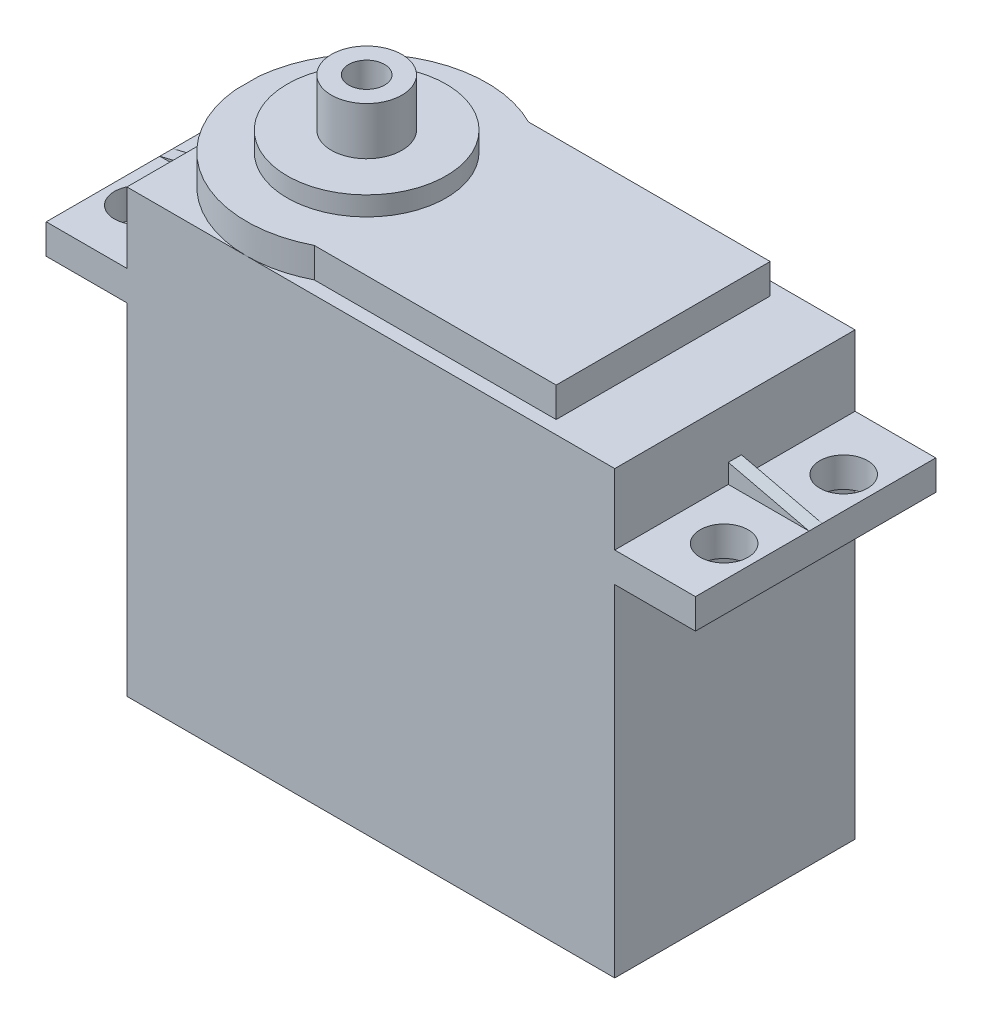
SolidWorks part; units mm, degrees
ref_plane "Plan de face" through (0, 0, 0) normal (0, 0, 1) x (1, 0, 0)
ref_plane "Plan de dessus" through (0, 0, 0) normal (0, 1, 0) x (1, 0, 0)
ref_plane "Plan de droite" through (0, 0, 0) normal (1, 0, 0) x (0, 0, -1)
sketch "Esquisse1" plane through (0, 0, 0) normal (0, 0, 1) x (1, 0, 0)
  line L0 (0, 0) -> (0, 3.4659) construction
  line L1 (-20.4, 10.9) -> (20.4, 10.9)
  line L2 (-20.4, 10.9) -> (-20.4, -28.5)
  line L3 (-20.4, -28.5) -> (20.4, -28.5)
  line L4 (20.4, 10.9) -> (20.4, -28.5)
  line L5 (-20.4, 2.5) -> (-27.15, 2.5)
  line L6 (-20.4, 2.5) -> (-20.4, 0)
  line L7 (-20.4, 0) -> (-27.15, 0)
  line L8 (-27.15, 2.5) -> (-27.15, 0)
  line L9 (20.4, 0) -> (27.15, 0)
  line L10 (27.15, 2.5) -> (27.15, 0)
  line L11 (20.4, 2.5) -> (27.15, 2.5)
  line L12 (20.4, 2.5) -> (20.4, 0)
  point P4 (0, 10.9)
  dimension "D1" = 2.5
  dimension "D2" = 54.3
  dimension "D3" = 40.8
  dimension "D4" = 28.5
  dimension "D5" = 39.4
extrude "Boss.-Extru.1" add sketch "Esquisse1" along normal mid plane 20.1
hole_wizard "Diamètre du perçage Ø4.0 (4)1" positions "Esquisse2" profile "Esquisse3" hole size "Ø4.0" standard "ISO" end condition up to next
sketch "Esquisse2" plane through (0, 2.5, 0) normal (0, 1, 0) x (1, 0, 0)
  line L0 (0, 0) -> (0, 4.6754) construction
  line L2 (0, 0) -> (4.2535, 0) construction
  point P0 (-24.5, 5)
  point P12 (24.5, 5)
  point P13 (24.5, -5)
  point P14 (-24.5, -5)
  dimension "D1" = 49
  dimension "D2" = 10
sketch "Esquisse3" plane through (-24.5, 2.5, -5) normal (1, 0, 0) x (0, 0, 1)
  line L0 (0, 0) -> (0, 2.5)
  line L1 (0, 2.5) -> (2, 2.5)
  line L2 (2, 2.5) -> (2, 0)
  line L5 (2, 0) -> (0, 0)
  line L11 (0, -6.35) -> (0, 107.95) construction
  dimension "Diamètre du perçage jusqu'au prochain" = 4
  dimension "Profondeur du perçage jusqu'au prochain" = 2.5
sketch "Esquisse5" plane through (0, 0, 0) normal (0, 0, 1) x (1, 0, 0)
  line L0 (-20.4, 4.1) -> (-27.15, 2.5)
  line L1 (-20.4, 10.9) -> (-20.4, 2.5) construction
  line L2 (-20.4, 2.5) -> (-27.15, 2.5) construction
  line L3 (-27.15, 2.5) -> (-20.4, 2.5)
  line L4 (-20.4, 2.5) -> (-20.4, 4.1)
  line L5 (0, 0) -> (0, 5.1704) construction
  line L6 (20.4, 2.5) -> (20.4, 4.1)
  line L7 (27.15, 2.5) -> (20.4, 2.5)
  line L8 (20.4, 4.1) -> (27.15, 2.5)
  dimension "D1" = 1.6
extrude "Boss.-Extru.3" add sketch "Esquisse5" along normal mid plane 1.1
sketch "Esquisse6" plane through (0, 10.9, 0) normal (0, 1, 0) x (1, 0, 0)
  line L0 (-20.4, 0.55) -> (-20.4, 10.05) construction
  circle A0 centre (-10.4, 0) radius 6.65
  dimension "D1" = 13.3
  dimension "D2" = 10
extrude "Boss.-Extru.4" add sketch "Esquisse6" along normal blind 1.6 contours A0
sketch "Esquisse4" plane through (0, 12.5, 0) normal (0, 1, 0) x (1, 0, 0)
  circle A0 centre (-10.4, 0) radius 2.95
  dimension "D2" = 5.9
extrude "Boss.-Extru.2" add sketch "Esquisse4" along normal blind 4
hole_wizard "Diamètre du perçage Ø3.0 (3)1" positions "Esquisse10" profile "Esquisse11" hole size "Ø3.0" standard "ISO"
sketch "Esquisse10" plane through (0, 16.5, 0) normal (0, 1, 0) x (1, 0, 0)
  point P0 (-10.4, 0)
sketch "Esquisse11" plane through (-10.4, 16.5, 0) normal (1, 0, 0) x (0, 0, 1)
  line L0 (0, 0) -> (0, 6.9013)
  line L1 (0, 6.9013) -> (1.5, 6)
  line L2 (1.5, 6) -> (1.5, 0)
  line L5 (1.5, 0) -> (0, 0)
  line L10 (0, 6.9013) -> (-1.5, 6) construction
  line L11 (0, -6.35) -> (0, 107.95) construction
  dimension "Diamètre du perçage" = 3
  dimension "Profondeur du perçage" = 6
  dimension "Angle de pointe" = 118
sketch "Esquisse7" plane through (0, 10.9, 0) normal (0, 1, 0) x (1, 0, 0)
  line L1 (-5.8283, 8.95) -> (14.4, 8.95)
  line L2 (-5.8283, 8.95) -> (-5.8283, -8.95) construction
  line L3 (-5.8283, -8.95) -> (14.4, -8.95)
  line L4 (14.4, 8.95) -> (14.4, -8.95)
  line L5 (20.4, -10.05) -> (20.4, 10.05) construction
  line L6 (-20.4, 10.05) -> (20.4, 10.05) construction
  circle A0 centre (-10.4, 0) radius 10.05
  point P6 (14.4, 0)
  line M6 (20.4, 10.05) -> (-20.4, 10.05)
  line M7 (-20.4, 10.05) -> (-20.4, -10.05)
  line M8 (-20.4, -10.05) -> (20.4, -10.05)
  line M9 (20.4, -10.05) -> (20.4, 10.05)
  dimension "D1" = 17.9
  dimension "D2" = 6
extrude "Enlèv. mat.-Extru.1" cut sketch "Esquisse7" against normal blind 2.5 contours A0 M6 M7 | A0 M7 M8 | A0 L1 L4 L3 M8 M9 M6
sketch "Esquisse8" plane through (-20.4, 0, 0) normal (-1, 0, 0) x (0, 0, 1)
  line L1 (-3.5, -20.5) -> (3.5, -20.5)
  line L2 (-3.5, -20.5) -> (-3.5, -24.7)
  line L3 (-3.5, -24.7) -> (3.5, -24.7)
  line L4 (3.5, -20.5) -> (3.5, -24.7)
  point P4 (0, -20.5)
  dimension "D1" = 4.2
  dimension "D2" = 7
  dimension "D3" = 20.5
extrude "Boss.-Extru.5" add sketch "Esquisse8" along normal blind 4.7
sketch "Esquisse9" plane through (-25.1, 0, 0) normal (-1, 0, 0) x (0, 0, 1)
  line L0 (0, 0) -> (0, -2.7747) construction
  line L1 (10.05, 0) -> (-10.05, 0) construction
  circle A0 centre (-1.5, -22.5238) radius 0.7
  circle A1 centre (0, -22.5238) radius 0.7
  circle A2 centre (1.5, -22.5238) radius 0.7
  dimension "D1" = 1.4
  dimension "D2" = 1.5
extrude "Boss.-Extru.6" add sketch "Esquisse9" along normal blind 3
